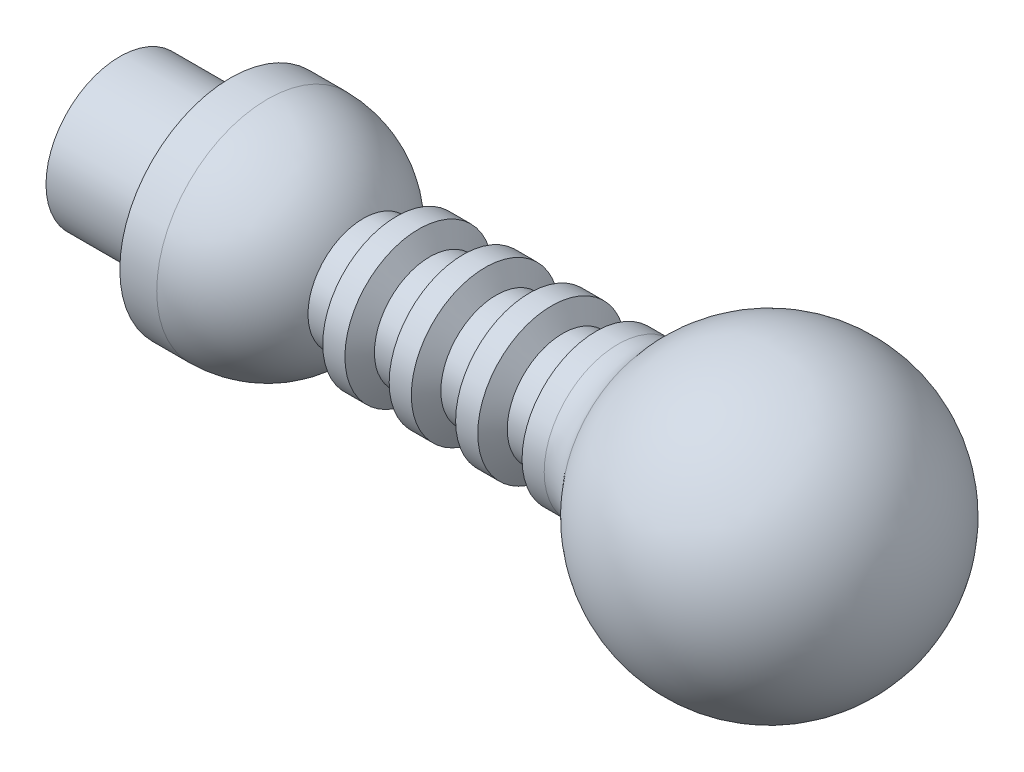
SolidWorks part; units mm, degrees
ref_plane "Front Plane" through (0, 0, 0) normal (0, 0, 1) x (1, 0, 0)
ref_plane "Top Plane" through (0, 0, 0) normal (0, 1, 0) x (1, 0, 0)
ref_plane "Right Plane" through (0, 0, 0) normal (1, 0, 0) x (0, 0, -1)
sketch "Sketch1" plane through (0, 0, 0) normal (0, 0, 1) x (1, 0, 0)
  line L0 (0, 0) -> (15425.7461, 0) construction
  line L1 (0, 0) -> (0, 10)
  line L2 (0, 10) -> (15, 10)
  line L3 (15, 10) -> (15, 15)
  line L4 (15, 15) -> (20, 15)
  line L5 (32.9904, 7.5) -> (35.9904, 7.5)
  line L6 (35.9904, 7.5) -> (37.4904, 10)
  line L7 (37.4904, 10) -> (40.4904, 10)
  line L8 (38.9904, 10) -> (38.9904, 0) construction
  line L9 (41.9904, 7.5) -> (40.4904, 10)
  line L10 (41.9904, 7.5) -> (44.9904, 7.5)
  line L11 (44.9904, 7.5) -> (46.4904, 10)
  line L12 (46.4904, 10) -> (49.4904, 10)
  line L13 (50.9904, 7.5) -> (49.4904, 10)
  line L14 (50.9904, 7.5) -> (53.9904, 7.5)
  line L15 (53.9904, 7.5) -> (55.4904, 10)
  line L16 (55.4904, 10) -> (58.4904, 10)
  line L17 (59.9904, 7.5) -> (58.4904, 10)
  line L18 (59.9904, 7.5) -> (62.9904, 7.5)
  line L19 (62.9904, 7.5) -> (64.4904, 10)
  line L20 (64.4904, 10) -> (67.4904, 10)
  line L21 (0, 0) -> (107.9843, 0)
  line L22 (68.9904, 7.5) -> (67.4904, 10) [skipped]
  arc A0 (20, 15) -> (32.9904, 7.5) centre (20, 0) cw
  arc A1 (67.4904, 10) -> (72.2197, 12.3077) centre (67.4904, 16) ccw
  arc A2 (72.2197, 12.3077) -> (107.9843, 0) centre (87.9843, 0) cw
  dimension "D1" = 15
  dimension "D11" = 6
  dimension "D12" = 20
  dimension "D2" = 5
  dimension "D3" = 15
  dimension "D4" = 20
  dimension "D5" = 1.5
  dimension "D6" = 3
  dimension "D7" = 3
  dimension "D8" = 20
  dimension "D9" = 15
  dimension "D10" = 4
revolve "Revolve1" add sketch "Sketch1" angle 360 about L0
